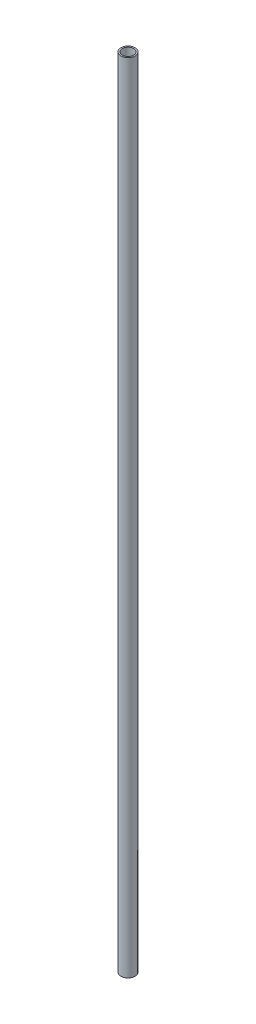
SolidWorks part; units mm, degrees
ref_plane "Front Plane" through (0, 0, 0) normal (0, 0, 1) x (1, 0, 0)
ref_plane "Top Plane" through (0, 0, 0) normal (0, 1, 0) x (1, 0, 0)
ref_plane "Right Plane" through (0, 0, 0) normal (1, 0, 0) x (0, 0, -1)
sketch "Sketch1" plane through (0, 0, 0) normal (0, 1, 0) x (1, 0, 0)
  circle A0 centre (0, 0) radius 3.175
  circle A1 centre (0, 0) radius 2.54
extrude "Boss-Extrude1" add sketch "Sketch1" along normal blind 355.6
